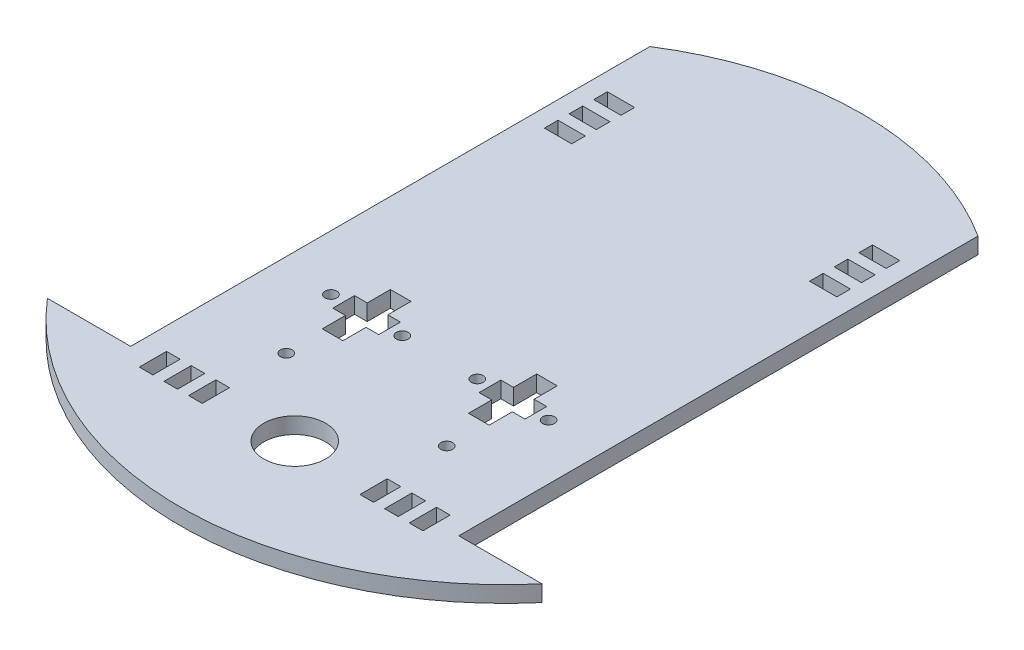
SolidWorks part; units mm, degrees
ref_plane "Alzado" through (0, 0, 0) normal (0, 0, 1) x (1, 0, 0)
ref_plane "Planta" through (0, 0, 0) normal (0, 1, 0) x (1, 0, 0)
ref_plane "Vista lateral" through (0, 0, 0) normal (1, 0, 0) x (0, 0, -1)
sketch "imagen_base" plane through (0, 0, 0) normal (0, 1, 0) x (1, 0, 0)
  line L0 (444.0596, 339.8572) -> (563.926, 337.7649) construction
  line L1 (-50.5587, 0) -> (50.5587, 0) construction
  line L2 (50.5587, 0) -> (50.5587, 160)
  line L3 (0, 0) -> (0, 174.7547) construction
  line L4 (-50.5587, 0) -> (-50.5587, 160)
  line L5 (-76.2, 0) -> (-50.5587, 0)
  line L6 (50.5587, 0) -> (76.2, 0)
  circle A0 centre (0, 0) radius 9.54
  arc A1 (50.5587, 160) -> (-50.5587, 160) centre (0, 80.7547) ccw
  arc A2 (-76.2, 0) -> (76.2, 0) centre (0, 64.7577) ccw
  point P6 (0, 0)
  dimension "D3" = 19.08
  dimension "D5" = 94
  dimension "D6" = 100
  dimension "D1" = 152.4
  dimension "D2" = 101.1174
  dimension "D4" = 160
sketch "Croquis3" plane through (0, 0, 0) normal (0, 1, 0) x (1, 0, 0)
  line L0 (50.5587, 0) -> (76.2, 0) construction
  line L1 (50.5587, 0) -> (50.5587, 160) construction
  line L2 (-50.5587, 0) -> (-50.5587, 160) construction
  line L3 (50.5587, 0) -> (76.2, 0)
  line L4 (50.5587, 0) -> (50.5587, 160)
  line L5 (-50.5587, 0) -> (-50.5587, 160)
  line L6 (-76.2, 0) -> (-50.5587, 0) construction
  line L7 (-76.2, 0) -> (-50.5587, 0)
  line L8 (0, 0) -> (0, 174.7547) construction
  line L9 (0, 0) -> (0, 174.7547) construction
  line L10 (36.6587, 133.8) -> (36.6587, 129.6)
  line L11 (36.6587, 126.2) -> (45.0587, 126.2)
  line L12 (36.6587, 126.2) -> (36.6587, 122)
  line L13 (36.6587, 122) -> (45.0587, 122)
  line L14 (45.0587, 126.2) -> (45.0587, 122)
  line L15 (36.6587, 133.8) -> (45.0587, 133.8)
  line L16 (45.0587, 133.8) -> (45.0587, 129.6)
  line L17 (36.6587, 129.6) -> (45.0587, 129.6)
  line L18 (36.6587, 141.4) -> (36.6587, 137.2)
  line L19 (36.6587, 141.4) -> (45.0587, 141.4)
  line L20 (45.0587, 141.4) -> (45.0587, 137.2)
  line L21 (36.6587, 137.2) -> (45.0587, 137.2)
  line L22 (-36.6587, 122) -> (-45.0587, 122)
  line L23 (-45.0587, 126.2) -> (-45.0587, 122)
  line L24 (-36.6587, 126.2) -> (-45.0587, 126.2)
  line L25 (-36.6587, 126.2) -> (-36.6587, 122)
  line L26 (-36.6587, 133.8) -> (-45.0587, 133.8)
  line L27 (-45.0587, 133.8) -> (-45.0587, 129.6)
  line L28 (-36.6587, 129.6) -> (-45.0587, 129.6)
  line L29 (-36.6587, 133.8) -> (-36.6587, 129.6)
  line L30 (-36.6587, 141.4) -> (-45.0587, 141.4)
  line L31 (-45.0587, 141.4) -> (-45.0587, 137.2)
  line L32 (-36.6587, 137.2) -> (-45.0587, 137.2)
  line L33 (-36.6587, 141.4) -> (-36.6587, 137.2)
  line L34 (31.8987, -4.2) -> (31.8987, 4.2)
  line L35 (39.4987, 4.2) -> (43.6987, 4.2)
  line L36 (28.4987, -4.2) -> (28.4987, 4.2)
  line L37 (36.0987, -4.2) -> (36.0987, 4.2)
  line L38 (39.4987, -4.2) -> (39.4987, 4.2)
  line L39 (24.2987, -4.2) -> (24.2987, 4.2)
  line L40 (31.8987, 4.2) -> (36.0987, 4.2)
  line L41 (24.2987, 4.2) -> (28.4987, 4.2)
  line L42 (24.2987, -4.2) -> (28.4987, -4.2)
  line L43 (39.4987, -4.2) -> (43.6987, -4.2)
  line L44 (43.6987, -4.2) -> (43.6987, 4.2)
  line L45 (31.8987, -4.2) -> (36.0987, -4.2)
  line L46 (39.4987, 4.2) -> (36.0987, 4.2) construction
  line L47 (31.8987, 4.2) -> (28.4987, 4.2) construction
  line L48 (28.4987, -4.2) -> (31.8987, -4.2) construction
  line L49 (36.0987, -4.2) -> (39.4987, -4.2) construction
  line L50 (45.0587, 126.2) -> (45.0587, 129.6) construction
  line L51 (45.0587, 133.8) -> (45.0587, 137.2) construction
  line L52 (43.6987, 0) -> (50.5587, 0) construction
  line L53 (-39.4987, -4.2) -> (-39.4987, 4.2)
  line L54 (-39.4987, -4.2) -> (-43.6987, -4.2)
  line L55 (-43.6987, -4.2) -> (-43.6987, 4.2)
  line L56 (-39.4987, 4.2) -> (-43.6987, 4.2)
  line L57 (-31.8987, -4.2) -> (-36.0987, -4.2)
  line L58 (-36.0987, -4.2) -> (-36.0987, 4.2)
  line L59 (-31.8987, 4.2) -> (-36.0987, 4.2)
  line L60 (-31.8987, -4.2) -> (-31.8987, 4.2)
  line L61 (-24.2987, -4.2) -> (-28.4987, -4.2)
  line L62 (-24.2987, -4.2) -> (-24.2987, 4.2)
  line L63 (-24.2987, 4.2) -> (-28.4987, 4.2)
  line L64 (-28.4987, -4.2) -> (-28.4987, 4.2)
  line L65 (19.3637, 34.2) -> (19.3637, 41.35)
  line L66 (19.3637, 34.2) -> (25.7137, 34.2)
  line L67 (25.7137, 34.2) -> (25.7137, 41.35)
  line L68 (25.7137, 41.35) -> (29.6087, 41.35)
  line L69 (29.6087, 41.35) -> (29.6087, 48.05)
  line L70 (29.6087, 48.05) -> (25.7137, 48.05)
  line L71 (25.7137, 48.05) -> (25.7137, 55.2)
  line L72 (25.7137, 55.2) -> (19.3637, 55.2)
  line L73 (22.5387, 55.2) -> (22.5387, 34.2) construction
  line L74 (19.3637, 41.35) -> (15.4687, 41.35)
  line L75 (15.4687, 41.35) -> (15.4687, 48.05)
  line L76 (15.4687, 48.05) -> (19.3637, 48.05)
  line L77 (19.3637, 48.05) -> (19.3637, 55.2)
  line L78 (29.6087, 44.7) -> (15.4687, 44.7) construction
  line L79 (-19.3637, 34.2) -> (-19.3637, 41.35)
  line L80 (-19.3637, 41.35) -> (-15.4687, 41.35)
  line L81 (-15.4687, 41.35) -> (-15.4687, 48.05)
  line L82 (-15.4687, 48.05) -> (-19.3637, 48.05)
  line L83 (-19.3637, 48.05) -> (-19.3637, 55.2)
  line L84 (-25.7137, 55.2) -> (-19.3637, 55.2)
  line L85 (-25.7137, 48.05) -> (-25.7137, 55.2)
  line L86 (-29.6087, 48.05) -> (-25.7137, 48.05)
  line L87 (-29.6087, 41.35) -> (-29.6087, 48.05)
  line L88 (-25.7137, 41.35) -> (-29.6087, 41.35)
  line L89 (-25.7137, 34.2) -> (-25.7137, 41.35)
  line L90 (-19.3637, 34.2) -> (-25.7137, 34.2)
  line L91 (29.6087, 44.7) -> (31.7087, 44.7) construction
  line L92 (26.5587, 22.125) -> (50.5587, 22.125) construction
  line L93 (24.7337, 23.95) -> (24.7337, 34.2) construction
  circle A0 centre (0, 0) radius 9.54 construction
  arc A1 (-76.2, 0) -> (76.2, 0) centre (0, 64.7577) ccw construction
  arc A2 (50.5587, 160) -> (-50.5587, 160) centre (0, 80.7547) ccw construction
  circle A3 centre (0, 0) radius 9.54
  arc A4 (-76.2, 0) -> (76.2, 0) centre (0, 64.7577) ccw
  arc A5 (50.5587, 160) -> (-50.5587, 160) centre (0, 80.7547) ccw
  circle A6 centre (33.5337, 44.7) radius 1.825
  circle A7 centre (11.5437, 44.7) radius 1.825
  circle A8 centre (-33.5337, 44.7) radius 1.825
  circle A9 centre (-11.5437, 44.7) radius 1.825
  circle A10 centre (24.7337, 22.125) radius 1.825
  circle A11 centre (-24.7337, 22.125) radius 1.825
  point P78 (22.5387, 44.7)
  dimension "D14" = 3.65
  dimension "D1" = 4.2
  dimension "D2" = 8.4
  dimension "D3" = 122
  dimension "D4" = 5.5
  dimension "D6" = 3.4
  dimension "D7" = 6.86
  dimension "D8" = 21
  dimension "D9" = 14.14
  dimension "D10" = 30
  dimension "D11" = 20.95
  dimension "D12" = 6.35
  dimension "D13" = 6.7
  dimension "D15" = 2.1
  dimension "D16" = 24
  dimension "D17" = 10.25
  dimension "D5" = 3
extrude "Saliente-Extruir1" add sketch "Croquis3" along normal blind 5
ref_plane "Plano1" through (0, 0, -44.7) normal (0, 0, 1) x (1, 0, 0)
